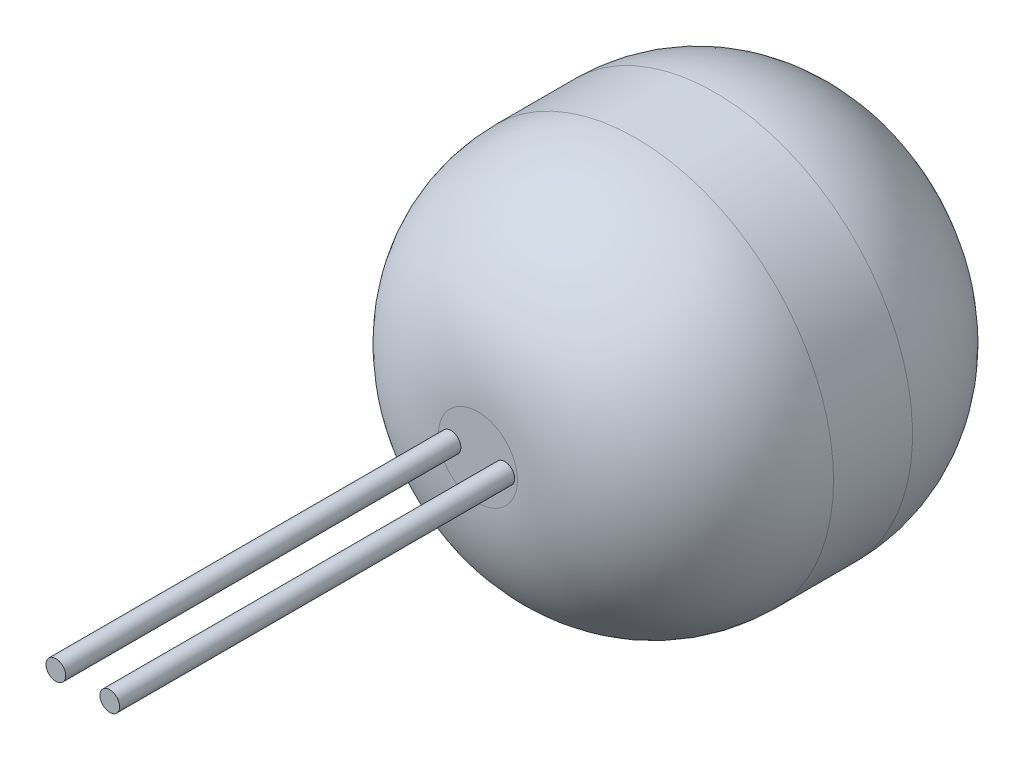
SolidWorks part; units mm, degrees
ref_plane "Alzado" through (0, 0, 0) normal (0, 0, 1) x (1, 0, 0)
ref_plane "Planta" through (0, 0, 0) normal (0, 1, 0) x (1, 0, 0)
ref_plane "Vista lateral" through (0, 0, 0) normal (1, 0, 0) x (0, 0, -1)
ref_plane "Plano1" through (0, 0, 0) normal (0, -1, 0) x (1, 0, 0)
sketch "Croquis1" plane through (0, 0, 0) normal (0, -1, 0) x (1, 0, 0)
  line L0 (1, 2) -> (0, 2)
  line L1 (0, 2) -> (0, 0)
  line L2 (0, 0) -> (1, 0)
  line L3 (1, 0) -> (1, 2)
  line L4 (0, 2) -> (0, 0) construction
revolve "Revolución1" add sketch "Croquis1" angle 360 about L4
sketch "Croquis2" plane through (0, 0, 2) normal (0, 0, 1) x (1, 0, 0)
  circle A0 centre (0.1362, 0) radius 0.05
extrude "Saliente-Extruir1" add sketch "Croquis2" along normal blind 2
sketch "Croquis3" plane through (0, 0, 2) normal (0, 0, 1) x (1, 0, 0)
  circle A0 centre (-0.1363, 0) radius 0.05
extrude "Saliente-Extruir2" add sketch "Croquis3" along normal blind 2
fillet "Redondeo1" radius 0.8 2 edges at (-1, 0, 0) (-1, 0, 2)
